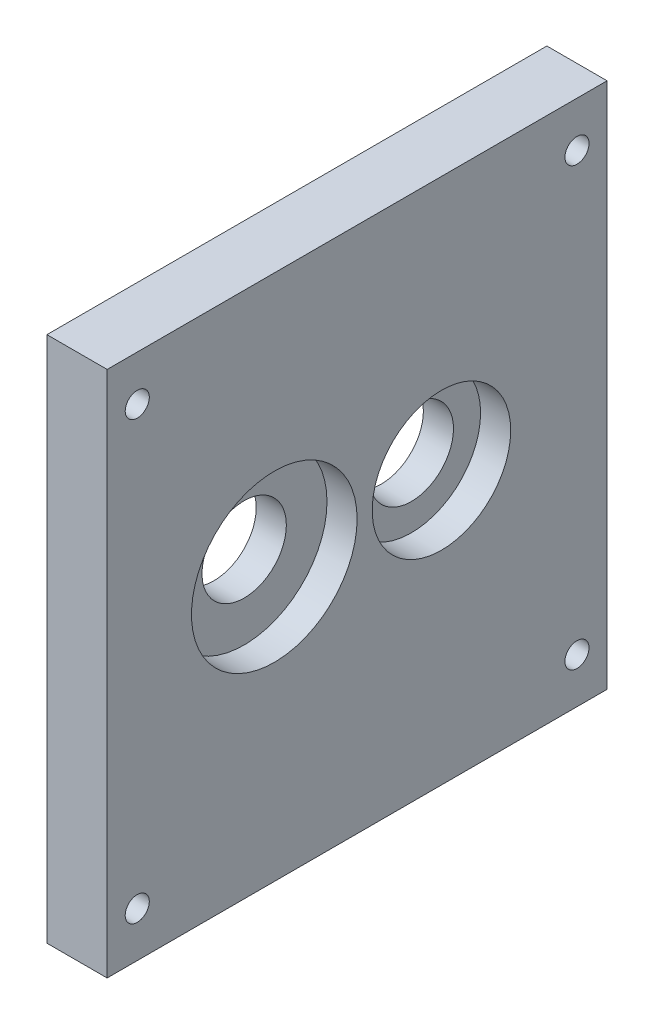
SolidWorks part; units mm, degrees
material "201 Annealed Stainless Steel (SS)"
ref_plane "Front Plane" through (0, 0, 0) normal (0, 0, 1) x (1, 0, 0)
ref_plane "Top Plane" through (0, 0, 0) normal (0, 1, 0) x (1, 0, 0)
ref_plane "Right Plane" through (0, 0, 0) normal (1, 0, 0) x (0, 0, -1)
sketch "Sketch1" plane through (0, 0, 0) normal (0, 1, 0) x (1, 0, 0)
  line L0 (-55, 0) -> (55, 0) construction
  line L1 (10, 83) -> (-10, 83)
  line L2 (10, 83) -> (10, -83)
  line L3 (10, -83) -> (-10, -83)
  line L4 (-10, 83) -> (-10, -83)
  line L5 (0, -55) -> (0, 55) construction
  point P6 (-10, 0)
  point P7 (0, -83)
  dimension "D1" = 166
  dimension "D2" = 20
extrude "Boss-Extrude1" add sketch "Sketch1" along normal blind 175
sketch "Sketch2" plane through (10, 0, 0) normal (1, 0, 0) x (0, 0, -1)
  circle A0 centre (-27.5, 90.5) radius 14 construction
  circle A1 centre (28, 90.5) radius 14 construction
  circle A2 centre (-27.5, 90.5) radius 14
  circle A3 centre (28, 90.5) radius 14
extrude "Cut-Extrude1" cut sketch "Sketch2" against normal blind 175
sketch "Sketch3" plane through (10, 0, 0) normal (1, 0, 0) x (0, 0, -1)
  circle A0 centre (-27.5, 90.5) radius 27.5 construction
  circle A1 centre (28, 90.5) radius 23 construction
  circle A2 centre (-27.5, 90.5) radius 27.5
  circle A3 centre (28, 90.5) radius 23
extrude "Cut-Extrude2" cut sketch "Sketch3" against normal blind 10
sketch "Sketch4" plane through (10, 0, 0) normal (1, 0, 0) x (0, 0, -1)
  line L0 (-83, 175) -> (83, 175) construction
  line L1 (83, 175) -> (83, 0) construction
  line L2 (83, 87.5) -> (-83, 87.5) construction
  line L3 (0, 87.5) -> (0, 175) construction
  circle A0 centre (73, 160) radius 4
  circle A1 centre (73, 15) radius 4
  circle A2 centre (-73, 15) radius 4
  circle A3 centre (-73, 160) radius 4
  dimension "D1" = 8
  dimension "D2" = 15
  dimension "D3" = 10
extrude "Cut-Extrude3" cut sketch "Sketch4" against normal through all
sketch "Sketch5" plane through (0, 0, 0) normal (0, -1, 0) x (1, 0, 0)
  line L0 (0, 0) -> (42.5301, 0) construction
  circle A0 centre (0, -50) radius 4
  circle A1 centre (0, 50) radius 4
  dimension "D1" = 8
  dimension "D2" = 100
extrude "Cut-Extrude4" cut sketch "Sketch5" against normal blind 15
